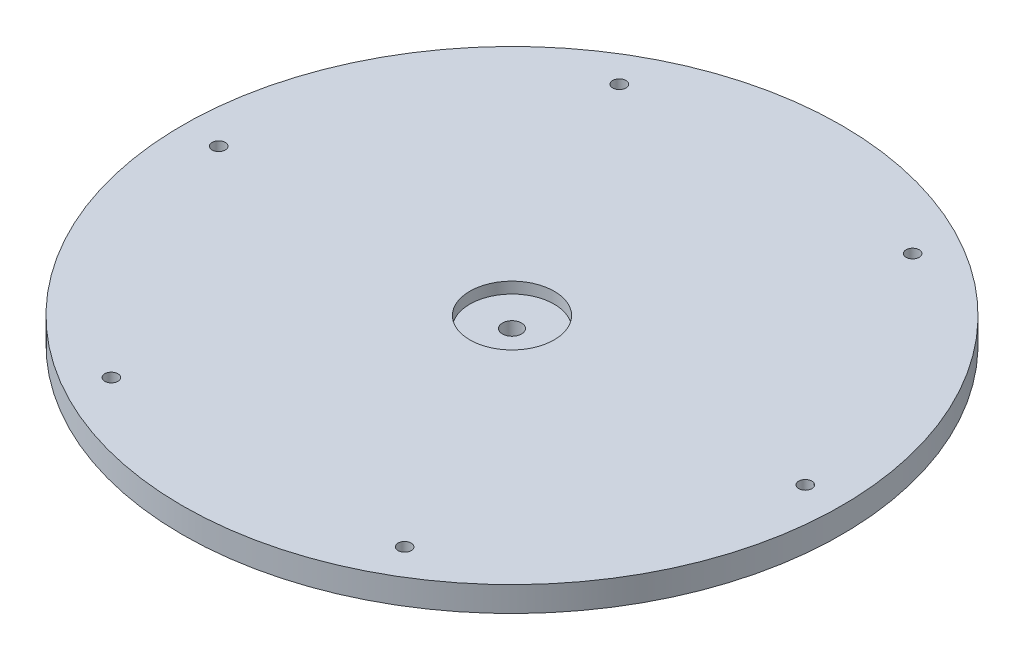
SolidWorks part; units mm, degrees
material "Pine"
ref_plane "Front Plane" through (0, 0, 0) normal (0, 0, 1) x (1, 0, 0)
ref_plane "Top Plane" through (0, 0, 0) normal (0, 1, 0) x (1, 0, 0)
ref_plane "Right Plane" through (0, 0, 0) normal (1, 0, 0) x (0, 0, -1)
sketch "Sketch1" plane through (0, 0, 0) normal (0, 1, 0) x (1, 0, 0)
  circle A0 centre (0, 0) radius 250
  circle A1 centre (0, 0) radius 7.25
  dimension "D1" = 500
  dimension "D2" = 14.5
extrude "Boss-Extrude1" add sketch "Sketch1" along normal mid plane 19
sketch "Sketch2" plane through (0, 9.5, 0) normal (0, 1, 0) x (1, 0, 0)
  circle A0 centre (0, 0) radius 32
  dimension "D1" = 64
extrude "Cut-Extrude1" cut sketch "Sketch2" against normal blind 8.5
sketch "Sketch3" plane through (0, -9.5, 0) normal (0, -1, 0) x (1, 0, 0)
  line L0 (-1000, 0) -> (49000, 0) construction
  line L1 (0, -1000) -> (0, 49000) construction
  line L2 (-500, 866.0254) -> (24500, -42435.2448) construction
  line L3 (-500, -866.0254) -> (24500, 42435.2448) construction
  circle A0 centre (111.25, 192.6907) radius 5
  circle A1 centre (222.5, 0) radius 5
  circle A2 centre (-111.25, -192.6907) radius 5
  circle A3 centre (-222.5, 0) radius 5
  circle A4 centre (-111.25, 192.6907) radius 5
  circle A5 centre (111.25, -192.6907) radius 5
  dimension "D1" = 10
  dimension "D2" = 10
  dimension "D3" = 222.5
  dimension "D4" = 222.5
extrude "Cut-Extrude2" cut sketch "Sketch3" against normal through all
